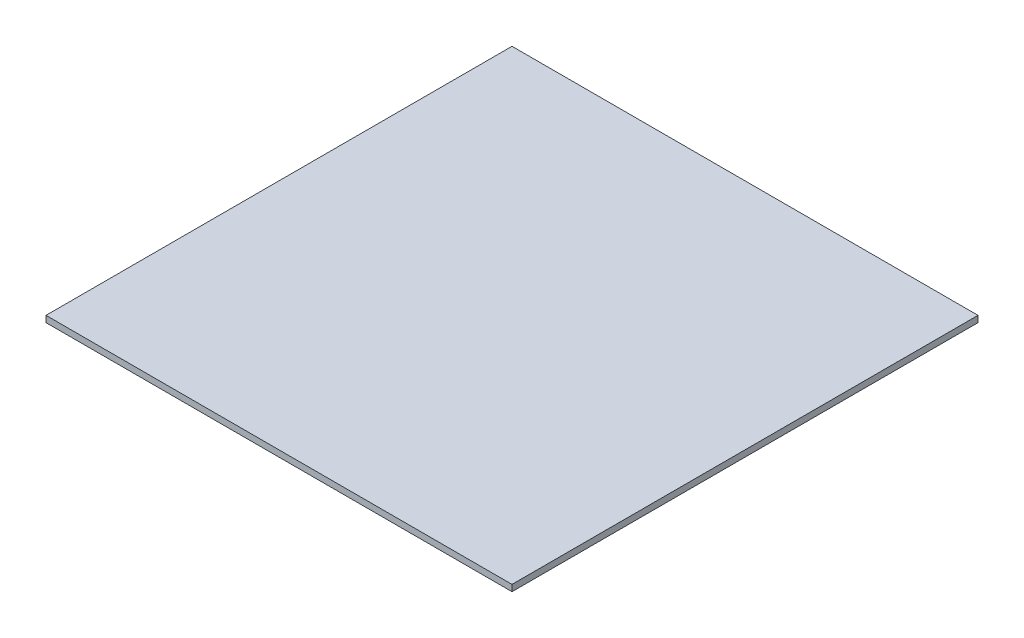
SolidWorks part; units mm, degrees
ref_plane "Front Plane" through (0, 0, 0) normal (0, 0, 1) x (1, 0, 0)
ref_plane "Top Plane" through (0, 0, 0) normal (0, 1, 0) x (1, 0, 0)
ref_plane "Right Plane" through (0, 0, 0) normal (1, 0, 0) x (0, 0, -1)
sketch "Sketch2" plane through (0, 0, 0) normal (0, 1, 0) x (1, 0, 0)
  line L1 (11, 11) -> (-11, 11)
  line L2 (11, 11) -> (11, -11)
  line L3 (11, -11) -> (-11, -11)
  line L4 (-11, 11) -> (-11, -11)
  line L5 (11, 11) -> (-11, -11) construction
  line L6 (11, -11) -> (-11, 11) construction
  point P0 (0, 0)
  dimension "D1" = 22
  dimension "D2" = 22
extrude "Boss-Extrude1" add sketch "Sketch2" along normal blind 0.3
